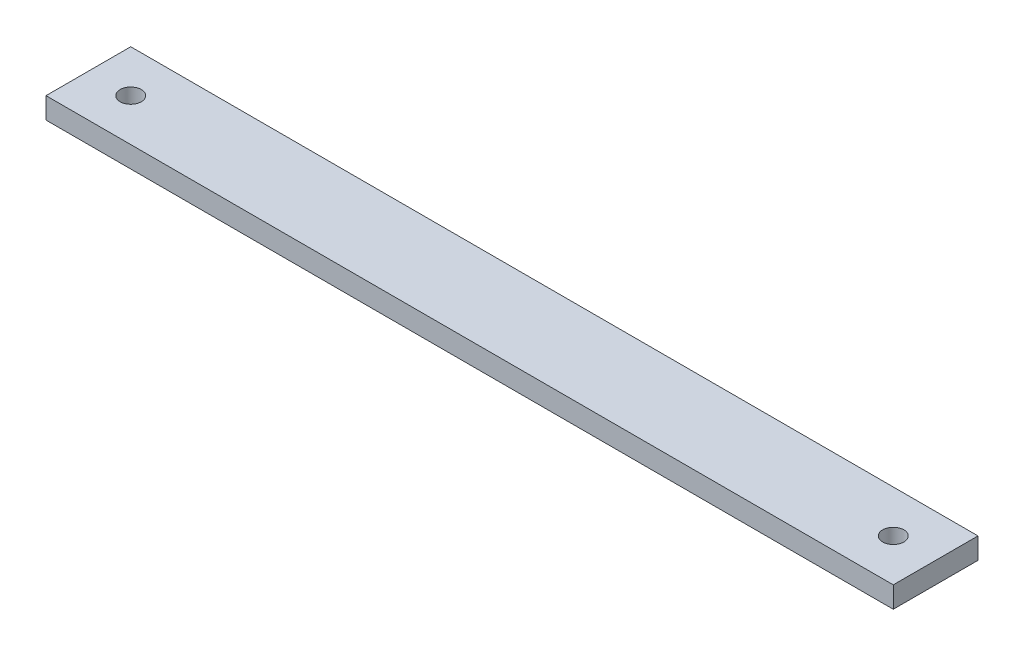
SolidWorks part; units mm, degrees
material "6061 Alloy"
ref_plane "Front Plane" through (0, 0, 0) normal (0, 0, 1) x (1, 0, 0)
ref_plane "Top Plane" through (0, 0, 0) normal (0, 1, 0) x (1, 0, 0)
ref_plane "Right Plane" through (0, 0, 0) normal (1, 0, 0) x (0, 0, -1)
sketch "Sketch1" plane through (0, 0, 0) normal (0, 1, 0) x (1, 0, 0)
  line L1 (0, 0) -> (-254, 0)
  line L2 (0, 0) -> (0, 25.4)
  line L3 (0, 25.4) -> (-254, 25.4)
  line L4 (-254, 0) -> (-254, 25.4)
  dimension "D2" = 25.4
  dimension "D1" = 254
extrude "Boss-Extrude1" add sketch "Sketch1" along normal blind 6.35
sketch "Sketch2" plane through (0, 6.35, 0) normal (0, 1, 0) x (1, 0, 0)
  line L0 (-127, 12.7) -> (-127, 25.4) construction
  line L1 (0, 25.4) -> (-254, 25.4) construction
  line L2 (-127, 12.7) -> (-127, 0) construction
  line L3 (-254, 0) -> (0, 0) construction
  circle A0 centre (-127, 12.7) radius 5.08
  dimension "D1" = 10.16
extrude "1/2-20 thread thru" [suppressed] cut sketch "Sketch2" against normal through all
sketch "Sketch3" plane through (0, 0, 0) normal (0, -1, 0) x (1, 0, 0)
  line L0 (-254, -12.7) -> (-215.9635, -12.7) construction
  line L1 (-254, -25.4) -> (-254, 0) construction
  line L2 (-254, -12.7) -> (-198.0565, -12.7) construction
  line L3 (0, -12.7) -> (-38.0365, -12.7) construction
  line L4 (0, 0) -> (0, -25.4) construction
  line L5 (0, -12.7) -> (-55.9435, -12.7) construction
  circle A0 centre (-38.0365, -12.7) radius 2.0193
  circle A1 centre (-55.9435, -12.7) radius 2.0193
  circle A2 centre (-215.9635, -12.7) radius 2.0193
  circle A3 centre (-198.0565, -12.7) radius 2.0193
  dimension "D3" = 4.0386
  dimension "D1" = 38.0365
  dimension "D2" = 55.9435
extrude "Cut-Extrude3" [suppressed] cut sketch "Sketch3" against normal blind 10.16
sketch "Sketch4" plane through (0, 0, 0) normal (0, -1, 0) x (1, 0, 0)
  line L2 (0, 0) -> (0, -25.4) construction
  line L3 (-254, -25.4) -> (-254, 0) construction
  circle A0 centre (-211.4804, -12.7) radius 4.1021
  circle A1 centre (-42.5196, -12.7) radius 4.1021
  dimension "D2" = 8.2042
  dimension "D1" = 42.5196
  dimension "D3" = 42.5196
extrude "Cut-Extrude4" [suppressed] cut sketch "Sketch4" against normal through all
hole_wizard "1/4 (0.25) Diameter Hole1" positions "Sketch6" profile "Sketch7" hole size "1/4" standard "ANSI Inch" end condition through all
sketch "Sketch6" plane through (0, 0, 0) normal (0, -1, 0) x (-1, 0, 0)
  line L0 (254, 25.4) -> (254, 0) construction
  line L2 (0, 25.4) -> (254, 25.4) construction
  line L3 (254, 0) -> (0, 0) construction
  line L4 (0, 0) -> (0, 25.4) construction
  point P0 (241.3, 12.7)
  point P3 (12.7, 12.7)
  dimension "D1" = 12.7
  dimension "D2" = 12.7
  dimension "D3" = 12.7
  dimension "D4" = 12.7
sketch "Sketch7" plane through (-241.3, 0, -12.7) normal (1, 0, 0) x (0, 0, -1)
  line L0 (0, 0) -> (0, 6.35)
  line L1 (0, 6.35) -> (3.175, 6.35)
  line L2 (3.175, 6.35) -> (3.175, 0)
  line L5 (3.175, 0) -> (0, 0)
  line L11 (0, -6.35) -> (0, 107.95) construction
  dimension "Thru Hole Dia." = 6.35
  dimension "Thru Hole Depth" = 6.35
hole_wizard "1/2-20 Tapped Hole3" positions "Sketch14" profile "Sketch15" tap size "1/2-20" standard "ANSI Inch"
sketch "Sketch14" [suppressed] plane through (0, 12.7, 0) normal (0, 1, 0) x (1, 0, 0)
  point P0 (-127, 12.7)
sketch "Sketch15" plane through (-127, 12.7, -12.7) normal (1, 0, 0) x (0, 0, 1)
  line L0 (0, 0) -> (0, 12.7)
  line L1 (0, 12.7) -> (5.7544, 12.7)
  line L2 (5.7544, 12.7) -> (5.7544, 0)
  line L5 (5.7544, 0) -> (0, 0)
  line L11 (0, -6.35) -> (0, 107.95) construction
  dimension "Thru Tap Drill Dia." = 11.5087
  dimension "Thru Tap Drill Depth" = 12.7
cosmetic thread "Hole Thread1"
sketch3d "Sketch_MAC1-1_TOPBEAM_MILLING" [suppressed]
  line L0 (-254, 0, -25.4) -> (-244, 0, -25.4)
  line L1 (-254, 0, -25.4) -> (-254, 0, -15.4)
  point P0 (-254, 0, -25.4)
  point P1 (-244, 0, -25.4)
  point P2 (-254, 0, -15.4)
sketch3d "Stock_TOPBEAM_MILLING"
  line L0 (-254, 12.7, -25.4) -> (0, 12.7, -25.4)
  line L1 (0, 12.7, -25.4) -> (0, 12.7, 0)
  line L2 (0, 12.7, 0) -> (-254, 12.7, 0)
  line L3 (-254, 12.7, 0) -> (-254, 12.7, -25.4)
  line L4 (-254, 0, -25.4) -> (0, 0, -25.4)
  line L5 (0, 0, -25.4) -> (0, 0, 0)
  line L6 (0, 0, 0) -> (-254, 0, 0)
  line L7 (-254, 0, 0) -> (-254, 0, -25.4)
  line L8 (-254, 12.7, -25.4) -> (-254, 0, -25.4)
  line L9 (0, 12.7, -25.4) -> (0, 0, -25.4)
  line L10 (0, 12.7, 0) -> (0, 0, 0)
  line L11 (-254, 12.7, 0) -> (-254, 0, 0)
  point P8 (-127, 12.7, -25.4)
  point P9 (0, 12.7, -12.7)
  point P10 (-127, 12.7, 0)
  point P11 (-254, 12.7, -12.7)
  point P12 (-127, 0, -25.4)
  point P13 (0, 0, -12.7)
  point P14 (-127, 0, 0)
  point P15 (-254, 0, -12.7)
  point P16 (-254, 6.35, -25.4)
  point P17 (0, 6.35, -25.4)
  point P18 (0, 6.35, 0)
  point P19 (-254, 6.35, 0)
  point P20 (-127, 6.35, -12.7)
  point P21 (-127, 6.35, -25.4)
  point P22 (-127, 0, -12.7)
  point P23 (-127, 6.35, 0)
  point P24 (-127, 12.7, -12.7)
  point P25 (-254, 6.35, -12.7)
  point P26 (0, 6.35, -12.7)
equation "\"cross_length\"=10"
equation "\"wing_spar_height\"= 2"
equation "\"wing_spar_thickness\"= .5"
equation "\"frame_width\"= 10"
equation "\"D1@Sketch1\"=\"frame_width\""
